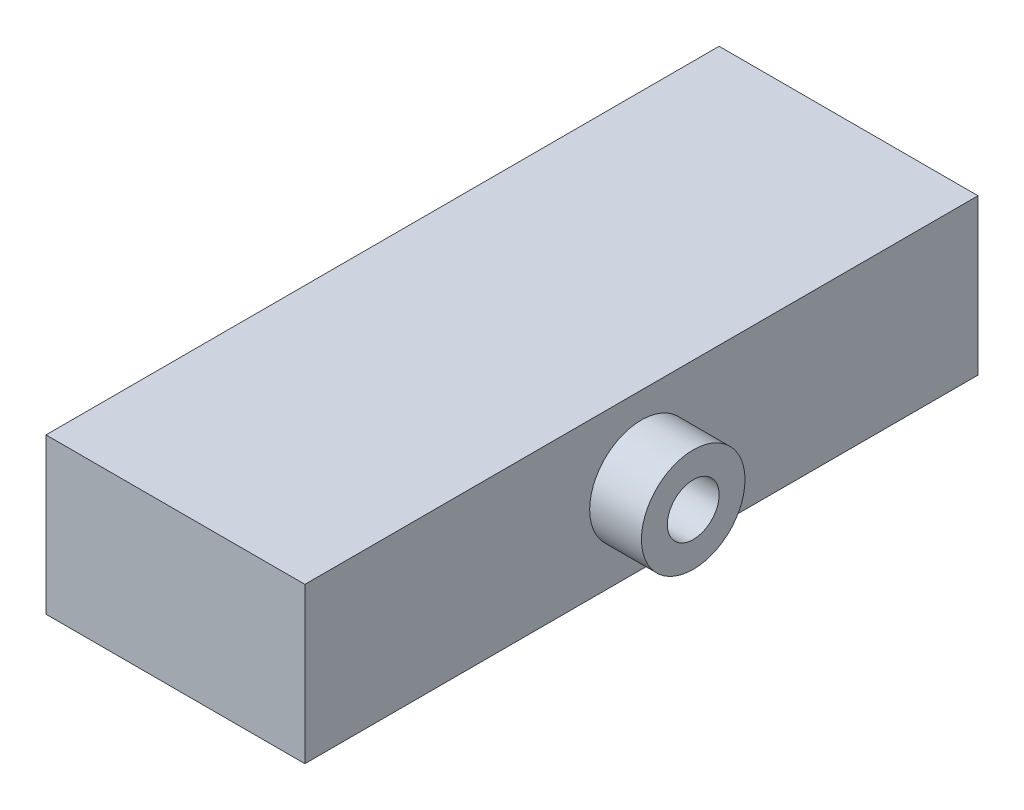
SolidWorks part; units mm, degrees
ref_plane "Front Plane" through (0, 0, 0) normal (0, 0, 1) x (1, 0, 0)
ref_plane "Top Plane" through (0, 0, 0) normal (0, 1, 0) x (1, 0, 0)
ref_plane "Right Plane" through (0, 0, 0) normal (1, 0, 0) x (0, 0, -1)
sketch "Sketch1" plane through (0, 0, 0) normal (0, 1, 0) x (1, 0, 0)
  line L1 (0, 0) -> (2.5, 0)
  line L2 (0, 0) -> (0, 6.5)
  line L3 (0, 6.5) -> (2.5, 6.5)
  line L4 (2.5, 0) -> (2.5, 6.5)
  dimension "D1" = 2.5
  dimension "D2" = 6.5
extrude "Boss-Extrude1" add sketch "Sketch1" along normal blind 1.5
sketch "Sketch2" plane through (2.5, 0, 0) normal (1, 0, 0) x (0, 0, -1)
  line L0 (3.25, 1.5) -> (3.25, 0.75) construction
  line L1 (0, 1.5) -> (6.5, 1.5) construction
  circle A0 centre (3.25, 0.75) radius 0.5
  circle A1 centre (3.25, 0.75) radius 0.25
  dimension "D2" = 0.5
  dimension "D3" = 1
  dimension "D1" = 0.75
extrude "Boss-Extrude2" add sketch "Sketch2" along normal blind 0.5
sketch "Sketch3" plane through (0, 0, 0) normal (-1, 0, 0) x (0, 0, 1)
  line L0 (-6.5, 1.5) -> (-6.5, 0) construction
sketch "Sketch4" plane through (0, 0, 0) normal (-1, 0, 0) x (0, 0, 1)
  line L0 (0, 0.75) -> (-0.75, 0.75) construction
  line L1 (0, 1.5) -> (0, 0) construction
  line L2 (-6.5, 0.75) -> (-5.75, 0.75) construction
  line L3 (-6.5, 1.5) -> (-6.5, 0) construction
  circle A0 centre (-5.75, 0.75) radius 0.25
  circle A1 centre (-0.75, 0.75) radius 0.25
  dimension "D3" = 0.5
  dimension "D4" = 0.5
  dimension "D1" = 0.75
  dimension "D2" = 0.75
extrude "Cut-Extrude1" cut sketch "Sketch4" against normal blind 0.5
